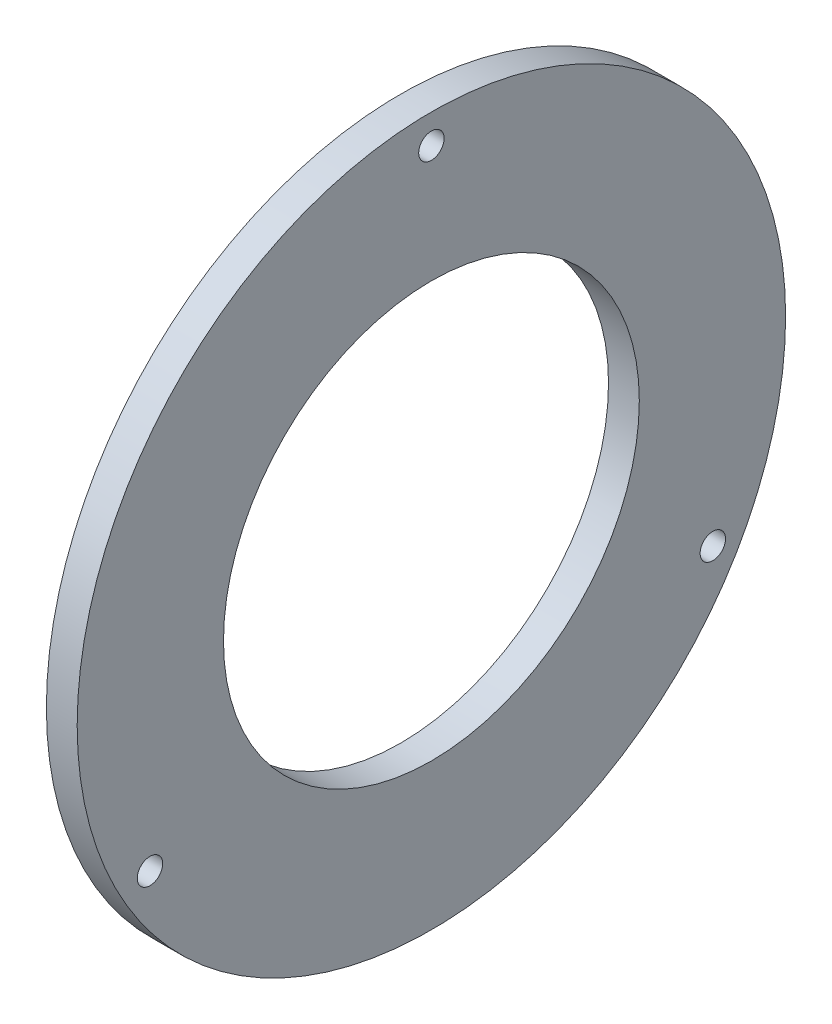
SolidWorks part; units mm, degrees
ref_plane "Front Plane" through (0, 0, 0) normal (0, 0, 1) x (1, 0, 0)
ref_plane "Top Plane" through (0, 0, 0) normal (0, 1, 0) x (1, 0, 0)
ref_plane "Right Plane" through (0, 0, 0) normal (1, 0, 0) x (0, 0, -1)
sketch "Axial profile (mm)" plane through (0, 0, 0) normal (0, 0, 1) x (1, 0, 0)
  line L0 (-110, 0) -> (75, 0) construction
  line L1 (131.7, 27) -> (135.7, 27)
  line L2 (135.7, 27) -> (135.7, 46)
  line L3 (135.7, 46) -> (131.7, 46)
  line L4 (131.7, 46) -> (131.7, 27)
revolve "Full revolution" add sketch "Axial profile (mm)" angle 360 about L0
sketch "Sketch2" plane through (0, 0, 0) normal (1, 0, 0) x (0, 0, -1)
  circle A0 centre (0, 42.2) radius 1.65
  circle A1 centre (-36.5463, -21.1) radius 1.65
  circle A2 centre (36.5463, -21.1) radius 1.65
extrude "Axial holes" cut sketch "Sketch2" along normal through all and the other way through all
